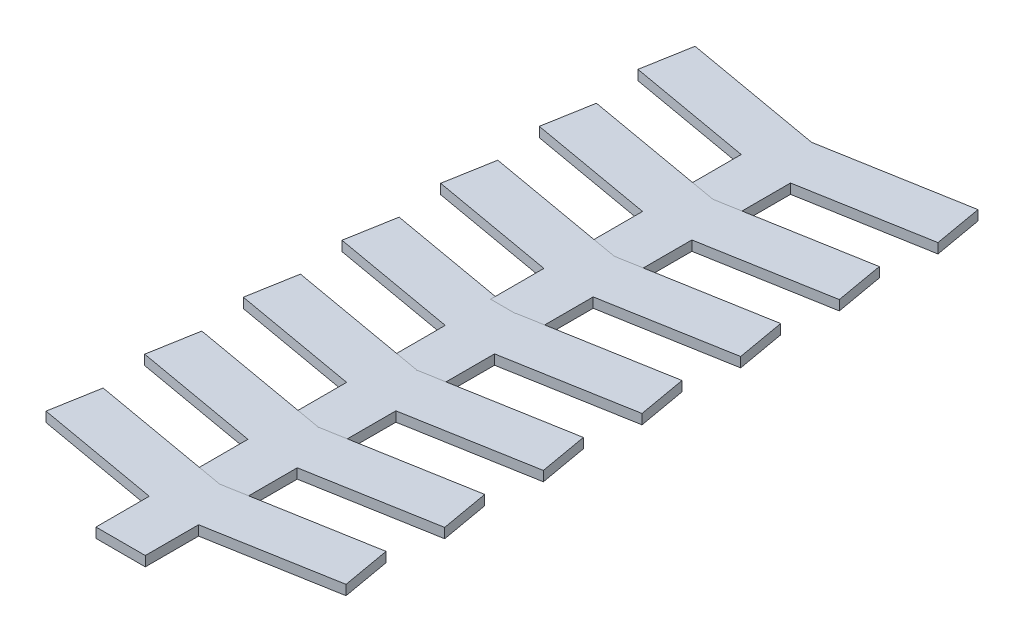
SolidWorks part; units mm, degrees
material "Rubber"
ref_plane "Front Plane" through (0, 0, 0) normal (0, 0, 1) x (1, 0, 0)
ref_plane "Top Plane" through (0, 0, 0) normal (0, 1, 0) x (1, 0, 0)
ref_plane "Right Plane" through (0, 0, 0) normal (1, 0, 0) x (0, 0, -1)
sketch "Sketch1" plane through (0, 0, 0) normal (0, 1, 0) x (1, 0, 0)
  line L0 (0, 0) -> (0, -15) construction
  line L3 (0, 0) -> (29.5442, 5.2094) construction
  line L12 (0, 0) -> (-29.5442, 5.2094) construction
  line L13 (29.5442, 5.2094) -> (30.4125, 0.2854) construction
  line L14 (29.5442, 5.2094) -> (28.676, 10.1335) construction
  line L15 (-29.5442, 5.2094) -> (-28.676, 10.1335) construction
  line L17 (-29.5442, 5.2094) -> (-30.4125, 0.2854) construction
  line L19 (0, -15) -> (5, -15) construction
  line L21 (0, -15) -> (-5, -15) construction
  line L43 (-28.676, 10.1335) -> (0, 5.0771)
  line L44 (28.676, 10.1335) -> (0, 5.0771)
  line L48 (-28.676, 10.1335) -> (-30.4125, 0.2854)
  line L51 (30.4125, 0.2854) -> (28.676, 10.1335)
  line L54 (-30.4125, 0.2854) -> (-5, -4.1955)
  line L55 (30.4125, 0.2854) -> (5, -4.1955)
  line L56 (-5, -4.1955) -> (-5, -15)
  line L57 (-5, -15) -> (5, -15)
  line L58 (5, -15) -> (5, -4.1955)
  dimension "D5" = 5
  dimension "D1" = 100
  dimension "D2" = 100
  dimension "D3" = 30
  dimension "D4" = 15
extrude "Boss-Extrude1" add sketch "Sketch1" along normal blind 2
pattern_linear "LPattern5" count 7 spacing 20 along (0, 0, 1) of bodies 102 159
